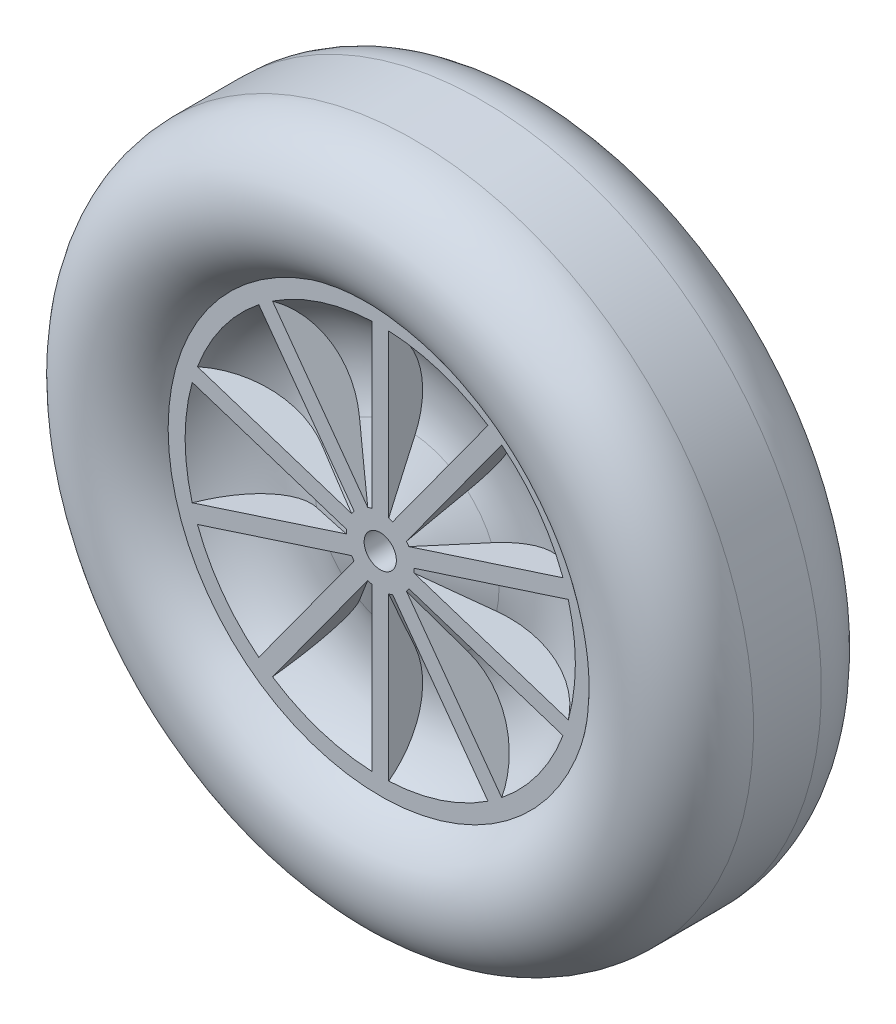
SolidWorks part; units mm, degrees
material "ABS"
ref_plane "Front Plane" through (0, 0, 0) normal (0, 0, 1) x (1, 0, 0)
ref_plane "Top Plane" through (0, 0, 0) normal (0, 1, 0) x (1, 0, 0)
ref_plane "Right Plane" through (0, 0, 0) normal (1, 0, 0) x (0, 0, -1)
sketch "Sketch5" plane through (0, 0, 0) normal (1, 0, 0) x (0, 0, -1)
  line L0 (-40, 0) -> (-40, 20)
  line L2 (-40, 20) -> (-40, 115) construction
  line L3 (-40, 115) -> (-40, 125)
  line L4 (-40, 125) -> (40, 125)
  line L5 (40, 125) -> (40, 115)
  line L6 (40, 115) -> (40, 20) construction
  line L8 (-40, 0) -> (40, 0)
  line L9 (-40, 115) -> (40, 115) construction
  line L10 (-40, 20) -> (40, 20) construction
  line L11 (40, 20) -> (40, 0)
  line L12 (-40, 20) -> (-24.4433, 54.3946)
  line L13 (40, 20) -> (24.4433, 54.3946)
  line L14 (-20, 75) -> (20, 75) construction
  arc A0 (-24.4433, 54.3946) -> (-40, 115) centre (-70, 75) ccw
  arc A1 (24.4433, 54.3946) -> (40, 115) centre (70, 75) cw
  dimension "D1" = 80
  dimension "D2" = 10
  dimension "D3" = 20
  dimension "D4" = 125
  dimension "D5" = 40
  dimension "D6" = 75
sketch "Sketch7" plane through (0, 0, 0) normal (1, 0, 0) x (0, 0, -1)
  line L0 (-40, 125) -> (40, 125)
  line L1 (-20, 200) -> (20, 200)
  line L3 (-20, 159.8333) -> (20, 159.8333) construction
  line L4 (0, 200) -> (0, 159.8333) construction
  line L5 (0, 159.8333) -> (0, 125) construction
  line L6 (-40, 125) -> (40, 125) construction
  line L7 (-40, 0) -> (40, 0) construction
  arc A0 (-20, 200) -> (-40, 125) centre (-20, 159.8333) ccw
  arc A1 (20, 200) -> (40, 125) centre (20, 159.8333) cw
  dimension "D1" = 200
  dimension "D2" = 40
ref_axis "Axis1" through (0, 0, -66.1833) along (0, 0, 1)
revolve "Revolve1" add sketch "Sketch5" angle 360 about axis through (0, 0, -66.1833) along (0, 0, 1)
sketch "Sketch8" plane through (0, 0, 0) normal (0, 0, 1) x (1, 0, 0)
  line L1 (-5, 0) -> (5, 0)
  line L2 (-5, 0) -> (-5, 120)
  line L3 (-5, 120) -> (5, 120)
  line L4 (5, 0) -> (5, 120)
  dimension "D1" = 10
  dimension "D2" = 120
extrude "Boss-Extrude1" add sketch "Sketch8" along normal mid plane 80
pattern_circular "CirPattern1" count 10 over 360 about axis through (0, 0, 0) along (0, 0, 1) of "Boss-Extrude1"
revolve "Revolve2" add sketch "Sketch7" angle 360 about axis through (0, 0, -66.1833) along (0, 0, 1)
sketch "Sketch9" plane through (0, 0, 40) normal (0, 0, 1) x (1, 0, 0)
  circle A0 centre (0, 0) radius 9.5
  dimension "D1" = 19
extrude "Cut-Extrude1" cut sketch "Sketch9" against normal through all
